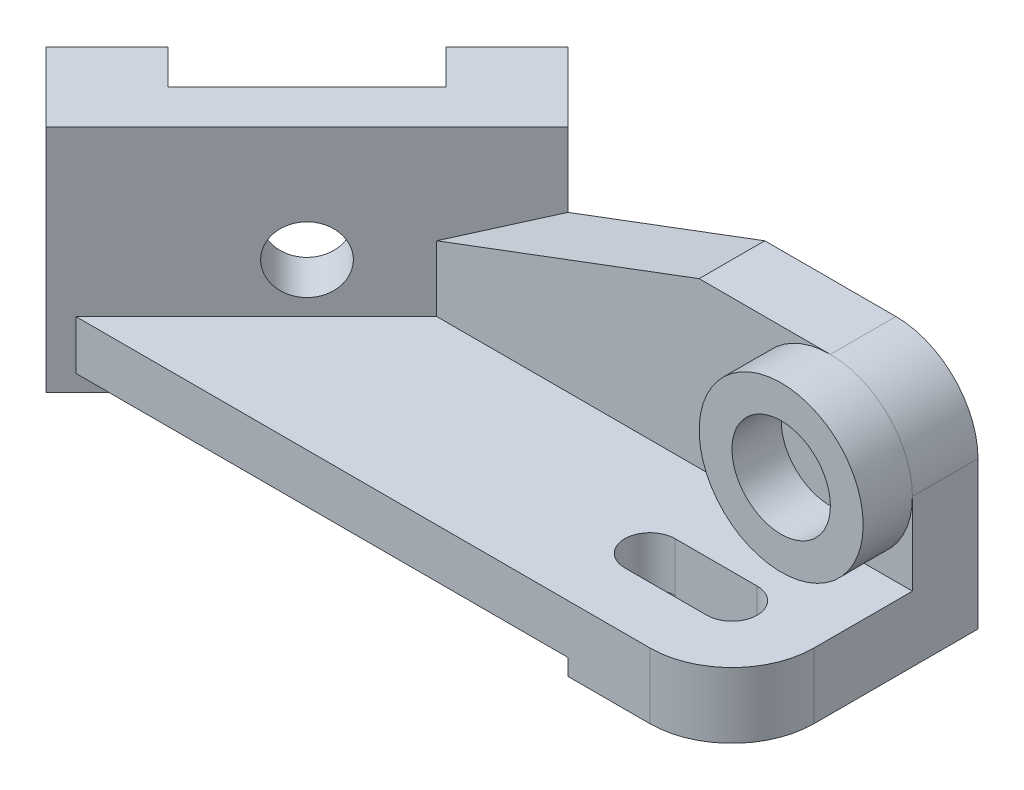
SolidWorks part; units mm, degrees
ref_plane "Front Plane" through (0, 0, 0) normal (0, 0, 1) x (1, 0, 0)
ref_plane "Top Plane" through (0, 0, 0) normal (0, 1, 0) x (1, 0, 0)
ref_plane "Right Plane" through (0, 0, 0) normal (1, 0, 0) x (0, 0, -1)
sketch "Sketch1" plane through (0, 0, 0) normal (0, 0, 1) x (1, 0, 0)
  line L0 (0, 0) -> (-100, 0)
  line L1 (-100, 0) -> (-100, 10)
  line L2 (-100, 10) -> (-400, 10)
  line L3 (-400, 10) -> (-400, 40)
  line L4 (-400, 40) -> (0, 40)
  line L5 (0, 40) -> (0, 0)
  dimension "D1" = 400
  dimension "D2" = 100
  dimension "D3" = 40
  dimension "D4" = 10
extrude "Boss-Extrude1" add sketch "Sketch1" against normal blind 150
fillet "Fillet1" radius 50 1 edges at (0, 20, 0)
sketch "Sketch3" plane through (0, 40, 0) normal (0, 1, 0) x (1, 0, 0)
  line L0 (-400, 0) -> (-250, 150)
  line L1 (0, 150) -> (-400, 150) construction
  line L2 (-250, 150) -> (-400, 150)
  line L3 (-400, 150) -> (-400, 0)
  dimension "D1" = 45
extrude "Cut-Extrude1" cut sketch "Sketch3" against normal up to next
sketch "Sketch4" plane through (0, 40, 0) normal (0, 1, 0) x (1, 0, 0)
  line L0 (-100, 0) -> (-100, 150) construction
  line L1 (-50, 0) -> (-400, 0) construction
  line L2 (0, 150) -> (-250, 150) construction
  line L3 (0, 150) -> (0, 50) construction
  line L4 (-50, 50) -> (-100, 50) construction
  line L5 (-50, 34.6214) -> (-100, 34.6214)
  line L6 (-50, 65.3786) -> (-100, 65.3786)
  arc A0 (-50, 34.6214) -> (-50, 65.3786) centre (-50, 50) ccw
  arc A1 (-100, 65.3786) -> (-100, 34.6214) centre (-100, 50) ccw
  arc A2 (-50, 0) -> (0, 50) centre (-50, 50) ccw construction
  point P10 (-75, 50)
  point P18 (-574.8032, 93.2584)
  dimension "D3" = 15.3786
  dimension "D1" = 100
  dimension "D2" = 50
extrude "Cut-Extrude2" cut sketch "Sketch4" against normal through all
sketch "Sketch5" plane through (0, 0, 0) normal (0, 1, 0) x (1, 0, 0)
  line L0 (-292.4264, 192.4264) -> (-250, 150)
  line L1 (-250, 150) -> (-409.099, -9.099)
  line L2 (-409.099, -9.099) -> (-451.5254, 33.3274)
  line L3 (-451.5254, 33.3274) -> (-414.4023, 70.4505)
  line L4 (-400, 0) -> (-250, 150) construction
  line L5 (-329.5495, 70.4505) -> (-371.9759, 112.8769) construction
  line L6 (-414.4023, 70.4505) -> (-393.1891, 49.2373)
  line L7 (-393.1891, 49.2373) -> (-308.3363, 134.0901)
  line L8 (-308.3363, 134.0901) -> (-329.5495, 155.3033)
  line L9 (-329.5495, 155.3033) -> (-292.4264, 192.4264)
  dimension "D1" = 225
  dimension "D2" = 60
  dimension "D3" = 0
  dimension "D4" = 30
  dimension "D5" = 120
extrude "Boss-Extrude2" add sketch "Sketch5" along normal blind 140
sketch "Sketch6" plane through (-209.099, 0, 209.099) normal (-0.7071, 0, 0.7071) x (0.7071, 0, 0.7071)
  line L0 (-282.8427, 70) -> (-342.8427, 70) construction
  line L1 (-282.8427, 140) -> (-282.8427, 0) construction
  line L2 (-342.8427, 140) -> (-342.8427, 0) construction
  line L3 (-342.8427, 120) -> (-312.8427, 100)
  line L4 (-312.8427, 100) -> (-312.8427, 40)
  line L5 (-312.8427, 40) -> (-342.8427, 20)
  line L6 (-342.8427, 20) -> (-342.8427, 120)
  dimension "D1" = 30
  dimension "D2" = 60
  dimension "D3" = 100
extrude "Cut-Extrude3" cut sketch "Sketch6" against normal blind 225
sketch "Sketch7" plane through (-221.2132, 0, -221.2132) normal (-0.7071, 0, -0.7071) x (-0.7071, 0, 0.7071)
  line L0 (70.7107, 70) -> (295.7107, 70) construction
  line L1 (70.7107, 40) -> (70.7107, 100) construction
  line L2 (295.7107, 40) -> (295.7107, 100) construction
  line L3 (183.2107, 140) -> (183.2107, 0) construction
  line L4 (123.2107, 140) -> (243.2107, 140) construction
  line L5 (123.2107, 0) -> (243.2107, 0) construction
  circle A0 centre (183.2107, 70) radius 20
  dimension "D1" = 40
extrude "Cut-Extrude4" cut sketch "Sketch7" against normal up to next
sketch "Sketch8" plane through (0, 40, 0) normal (0, 1, 0) x (1, 0, 0)
  line L0 (0, 150) -> (0, 110)
  line L1 (0, 150) -> (0, 50) construction
  line L2 (0, 110) -> (-290, 110)
  line L3 (-250, 150) -> (-400, 0) construction
  line L4 (-290, 110) -> (-250, 150)
  line L5 (0, 150) -> (-250, 150) construction
  line L6 (-250, 150) -> (0, 150)
  dimension "D1" = 40
extrude "Boss-Extrude3" add sketch "Sketch8" along normal up to surface (100 mm away) up to face at (-356.066, 140, -96.967)
sketch "Sketch11" plane through (0, 0, -110) normal (0, 0, 1) x (1, 0, 0)
  line L0 (0, 140) -> (0, 40) construction
  line L1 (0, 140) -> (-290, 140) construction
  circle A0 centre (-50, 90) radius 50
  dimension "D3" = 100
  dimension "D1" = 50
  dimension "D2" = 50
extrude "Boss-Extrude9" add sketch "Sketch11" along normal blind 30 draft 0.01
fillet "Fillet3" radius 50 1 edges at (0, 140, -130)
sketch "Sketch12" plane through (0, 0, -110) normal (0, 0, 1) x (1, 0, 0)
  circle A0 centre (-50, 90) radius 30
  circle A1 centre (-50, 90) radius 49.9948 construction
  dimension "D1" = 60
extrude "Cut-Extrude5" cut sketch "Sketch12" along normal blind 30
sketch "Sketch13" plane through (0, 0, -110) normal (0, 0, 1) x (1, 0, 0)
  line L0 (-290, 80) -> (-130, 140)
  line L1 (-290, 140) -> (-290, 40) construction
  line L2 (-50, 140) -> (-290, 140) construction
  line L3 (-130, 140) -> (-290, 140)
  line L4 (-290, 140) -> (-290, 80)
  dimension "D1" = 160
  dimension "D2" = 60
extrude "Cut-Extrude7" cut sketch "Sketch13" against normal up to next
sketch "Sketch16" plane through (0, 140, 0) normal (0, 1, 0) x (1, 0, 0)
  line L0 (-290, 110) -> (-250, 150)
  line L1 (-250, 150) -> (-271.2132, 171.2132) construction
  line L2 (-250, 150) -> (-290, 190)
  line L3 (-290, 190) -> (-290, 110)
extrude "Boss-Extrude11" add sketch "Sketch16" against normal up to surface (45 mm away)
sketch "Sketch17" plane through (-50, 0, 50) normal (0.7071, 0, -0.7071) x (-0.7071, 0, -0.7071)
  line L0 (312.8427, 80) -> (312.8427, 100)
  line L1 (312.8427, 100) -> (339.4113, 117.7124)
  line L2 (339.4113, 117.7124) -> (339.4113, 80)
  line L3 (339.4113, 80) -> (312.8427, 80)
extrude "Cut-Extrude8" cut sketch "Sketch17" against normal through all
